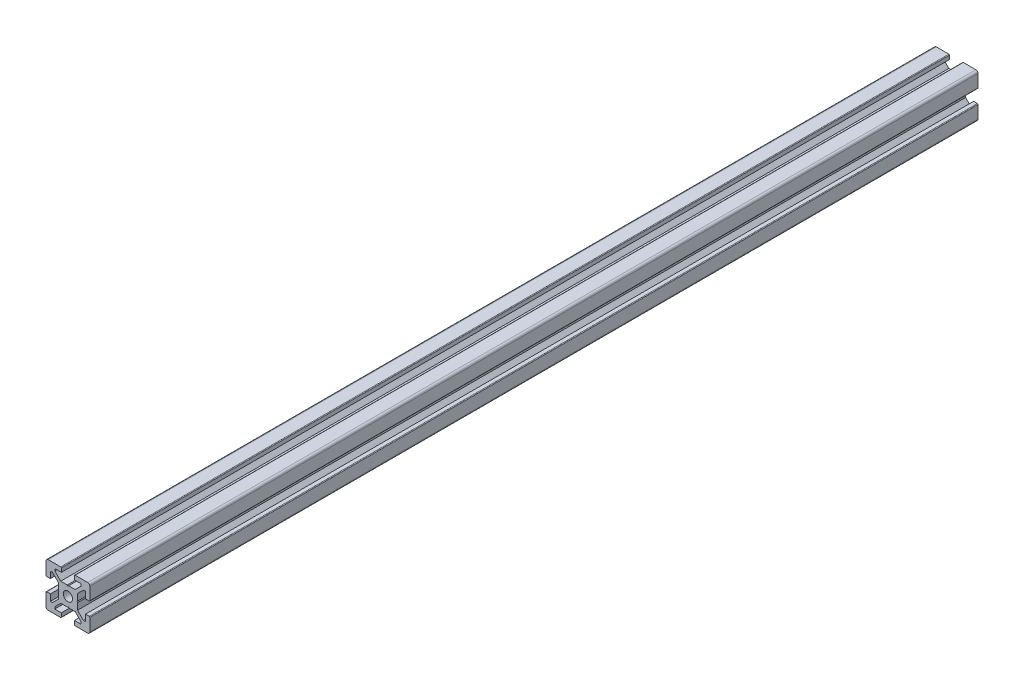
SolidWorks part; units mm, degrees
ref_plane "Front Plane" through (0, 0, 0) normal (0, 0, 1) x (1, 0, 0)
ref_plane "Top Plane" through (0, 0, 0) normal (0, 1, 0) x (1, 0, 0)
ref_plane "Right Plane" through (0, 0, 0) normal (1, 0, 0) x (0, 0, -1)
sketch "Sketch1" plane through (0, 0, 0) normal (0, 0, 1) x (1, 0, 0)
  line L0 (0, 0) -> (0, 4.3607) construction
  line L1 (-10, 10) -> (10, 10) construction
  line L2 (-10, 10) -> (-10, -10) construction
  line L3 (-10, -10) -> (10, -10) construction
  line L4 (10, 10) -> (10, -10) construction
  line L5 (-10, 10) -> (10, -10) construction
  line L6 (-10, -10) -> (10, 10) construction
  line L7 (0, 4.3607) -> (3.3, 4.3607) construction
  line L8 (3.3, 4.3607) -> (6, 7.0607)
  line L9 (6, 7.0607) -> (6, 8)
  line L10 (6, 8) -> (3, 8)
  line L11 (3, 8) -> (3, 9.7)
  line L12 (3.3, 10) -> (9, 10)
  line L13 (0, 4.0607) -> (0.3, 4.3607)
  line L14 (0.3, 4.3607) -> (3.3, 4.3607)
  line L15 (10, 3.3) -> (10, 9)
  line L16 (8, 3) -> (9.7, 3)
  line L17 (8, 6) -> (8, 3)
  line L18 (7.0607, 6) -> (8, 6)
  line L19 (4.3607, 3.3) -> (7.0607, 6)
  line L20 (4.3607, 0.3) -> (4.3607, 3.3)
  line L21 (4.0607, 0) -> (4.3607, 0.3)
  line L22 (4.0607, 0) -> (4.3607, -0.3)
  line L23 (4.3607, -0.3) -> (4.3607, -3.3)
  line L24 (4.3607, -3.3) -> (7.0607, -6)
  line L25 (7.0607, -6) -> (8, -6)
  line L26 (8, -6) -> (8, -3)
  line L27 (8, -3) -> (9.7, -3)
  line L28 (10, -3.3) -> (10, -9)
  line L29 (3.3, -10) -> (9, -10)
  line L30 (3, -8) -> (3, -9.7)
  line L31 (6, -8) -> (3, -8)
  line L32 (6, -7.0607) -> (6, -8)
  line L33 (3.3, -4.3607) -> (6, -7.0607)
  line L34 (0.3, -4.3607) -> (3.3, -4.3607)
  line L35 (0, -4.0607) -> (0.3, -4.3607)
  line L36 (0, -4.0607) -> (-0.3, -4.3607)
  line L37 (-0.3, -4.3607) -> (-3.3, -4.3607)
  line L38 (-3.3, -4.3607) -> (-6, -7.0607)
  line L39 (-6, -7.0607) -> (-6, -8)
  line L40 (-6, -8) -> (-3, -8)
  line L41 (-3, -8) -> (-3, -9.7)
  line L42 (-3.3, -10) -> (-9, -10)
  line L43 (-10, -3.3) -> (-10, -9)
  line L44 (-8, -3) -> (-9.7, -3)
  line L45 (-8, -6) -> (-8, -3)
  line L46 (-7.0607, -6) -> (-8, -6)
  line L47 (-4.3607, -3.3) -> (-7.0607, -6)
  line L48 (-4.3607, -0.3) -> (-4.3607, -3.3)
  line L49 (-4.0607, 0) -> (-4.3607, -0.3)
  line L50 (-4.0607, 0) -> (-4.3607, 0.3)
  line L51 (-4.3607, 0.3) -> (-4.3607, 3.3)
  line L52 (-4.3607, 3.3) -> (-7.0607, 6)
  line L53 (-7.0607, 6) -> (-8, 6)
  line L54 (-8, 6) -> (-8, 3)
  line L55 (-8, 3) -> (-9.7, 3)
  line L56 (-10, 3.3) -> (-10, 9)
  line L57 (-3.3, 10) -> (-9, 10)
  line L58 (-3, 8) -> (-3, 9.7)
  line L59 (-6, 8) -> (-3, 8)
  line L60 (-6, 7.0607) -> (-6, 8)
  line L61 (-3.3, 4.3607) -> (-6, 7.0607)
  line L62 (-0.3, 4.3607) -> (-3.3, 4.3607)
  line L63 (0, 4.0607) -> (-0.3, 4.3607)
  arc A0 (3, 9.7) -> (3.3, 10) centre (3.3, 9.7) cw
  arc A1 (9, 10) -> (10, 9) centre (9, 9) cw
  arc A2 (9.7, 3) -> (10, 3.3) centre (9.7, 3.3) ccw
  arc A3 (9.7, -3) -> (10, -3.3) centre (9.7, -3.3) cw
  arc A4 (10, -9) -> (9, -10) centre (9, -9) cw
  arc A5 (3, -9.7) -> (3.3, -10) centre (3.3, -9.7) ccw
  arc A6 (-3, -9.7) -> (-3.3, -10) centre (-3.3, -9.7) cw
  arc A7 (-9, -10) -> (-10, -9) centre (-9, -9) cw
  arc A8 (-9.7, -3) -> (-10, -3.3) centre (-9.7, -3.3) ccw
  arc A9 (-9.7, 3) -> (-10, 3.3) centre (-9.7, 3.3) cw
  arc A10 (-10, 9) -> (-9, 10) centre (-9, 9) cw
  arc A11 (-3, 9.7) -> (-3.3, 10) centre (-3.3, 9.7) ccw
  circle A12 centre (0, 0) radius 2.1
  point P0 (0, 0)
  point P95 (0, 0)
  dimension "D4" = 1
  dimension "D5" = 0.3
  dimension "D12" = 4.2
  dimension "D1" = 20
  dimension "D2" = 20
  dimension "D3" = 2
  dimension "D6" = 0.75
  dimension "D7" = 3
  dimension "D8" = 0.9393
  dimension "D9" = 3
  dimension "D10" = 0.3
  dimension "D11" = 4
extrude "Boss-Extrude1" add sketch "Sketch1" along normal blind 404.96
